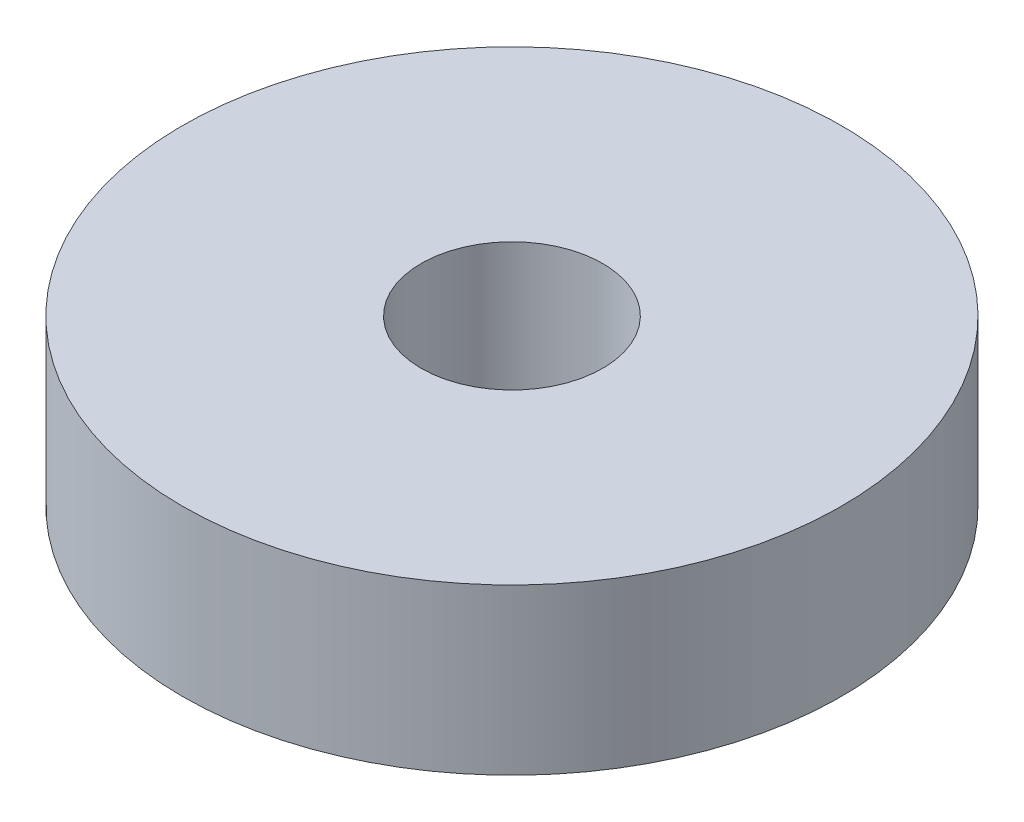
SolidWorks part; units mm, degrees
ref_plane "Front Plane" through (0, 0, 0) normal (0, 0, 1) x (1, 0, 0)
ref_plane "Top Plane" through (0, 0, 0) normal (0, 1, 0) x (1, 0, 0)
ref_plane "Right Plane" through (0, 0, 0) normal (1, 0, 0) x (0, 0, -1)
sketch "Sketch1" plane through (0, 0, 0) normal (0, 1, 0) x (1, 0, 0)
  circle A0 centre (0, 0) radius 6.35
  circle A1 centre (0, 0) radius 1.75
  dimension "D1" = 12.7
  dimension "D2" = 3.5
extrude "Boss-Extrude1" add sketch "Sketch1" along normal blind 3.175
